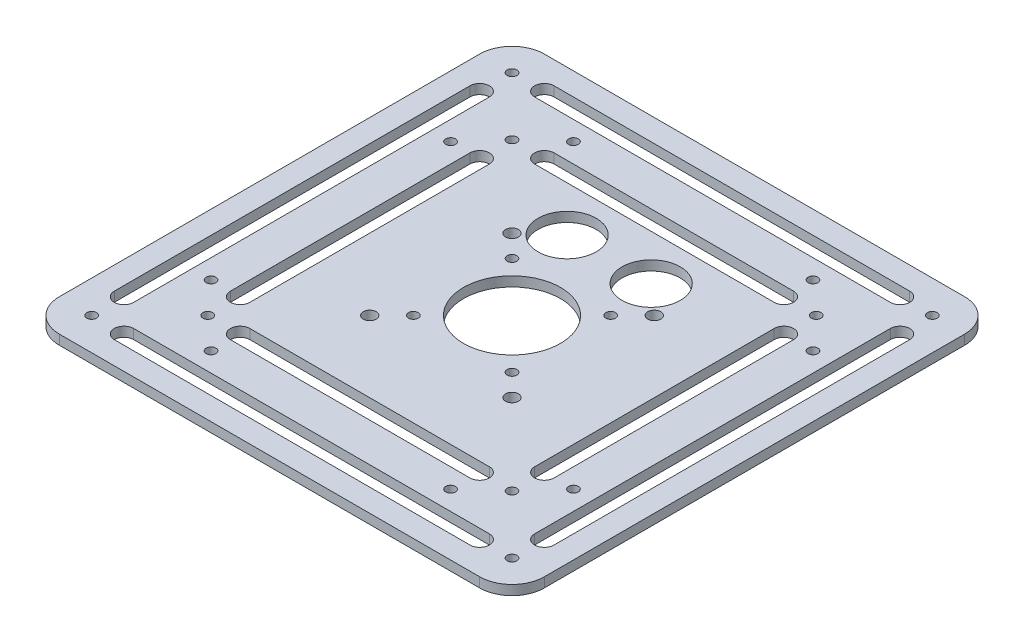
SolidWorks part; units mm, degrees
ref_plane "Front Plane" through (0, 0, 0) normal (0, 0, 1) x (1, 0, 0)
ref_plane "Top Plane" through (0, 0, 0) normal (0, 1, 0) x (1, 0, 0)
ref_plane "Right Plane" through (0, 0, 0) normal (1, 0, 0) x (0, 0, -1)
sketch "Sketch1" plane through (0, 0, 0) normal (0, 1, 0) x (1, 0, 0)
  line L0 (0, 0) -> (0, 75) construction
  line L1 (-65, -75) -> (65, -75)
  line L2 (-75, -65) -> (-75, 65)
  line L3 (-65, 75) -> (65, 75)
  line L4 (75, -65) -> (75, 65)
  line L5 (-75, -75) -> (75, 75) construction
  line L6 (-75, 75) -> (75, -75) construction
  line L7 (0, 0) -> (0, -75) construction
  line L8 (0, 0) -> (75, 0) construction
  line L9 (0, 0) -> (-75, 0) construction
  line L10 (-47.0395, 37.0395) -> (-47.0395, -37.0395) construction
  line L11 (-44.0395, 37.0395) -> (-44.0395, -37.0395)
  line L12 (-50.0395, 37.0395) -> (-50.0395, -37.0395)
  line L13 (47.0395, 37.0395) -> (47.0395, -37.0395) construction
  line L14 (44.0395, 37.0395) -> (44.0395, -37.0395)
  line L15 (50.0395, 37.0395) -> (50.0395, -37.0395)
  line L16 (-37.0395, 47.0395) -> (37.0395, 47.0395) construction
  line L17 (-37.0395, 44.0395) -> (37.0395, 44.0395)
  line L18 (-37.0395, 50.0395) -> (37.0395, 50.0395)
  line L19 (37.0395, -47.0395) -> (-37.0395, -47.0395) construction
  line L20 (37.0395, -44.0395) -> (-37.0395, -44.0395)
  line L21 (37.0395, -50.0395) -> (-37.0395, -50.0395)
  line L22 (-65, 55) -> (-65, -55) construction
  line L23 (-62, 55) -> (-62, -55)
  line L24 (-68, 55) -> (-68, -55)
  line L25 (65, 55) -> (65, -55) construction
  line L26 (62, 55) -> (62, -55)
  line L27 (68, 55) -> (68, -55)
  line L28 (-55, 65) -> (55, 65) construction
  line L29 (-55, 62) -> (55, 62)
  line L30 (-55, 68) -> (55, 68)
  line L31 (55, -65) -> (-55, -65) construction
  line L32 (55, -62) -> (-55, -62)
  line L33 (55, -68) -> (-55, -68)
  arc A0 (-65, -75) -> (-75, -65) centre (-65, -65) cw
  arc A1 (65, -75) -> (75, -65) centre (65, -65) ccw
  arc A2 (65, 75) -> (75, 65) centre (65, 65) cw
  arc A3 (-75, 65) -> (-65, 75) centre (-65, 65) cw
  circle A4 centre (65, 65) radius 1.5
  circle A5 centre (47.0395, 47.0395) radius 1.5
  circle A6 centre (-65, 65) radius 1.5
  circle A7 centre (-47.0395, 47.0395) radius 1.5
  circle A8 centre (65, -65) radius 1.5
  circle A9 centre (47.0395, -47.0395) radius 1.5
  circle A10 centre (-65, -65) radius 1.5
  circle A11 centre (-47.0395, -47.0395) radius 1.5
  circle A12 centre (0, 0) radius 15
  arc A13 (-44.0395, 37.0395) -> (-50.0395, 37.0395) centre (-47.0395, 37.0395) ccw
  arc A14 (-50.0395, -37.0395) -> (-44.0395, -37.0395) centre (-47.0395, -37.0395) ccw
  arc A15 (44.0395, 37.0395) -> (50.0395, 37.0395) centre (47.0395, 37.0395) cw
  arc A16 (50.0395, -37.0395) -> (44.0395, -37.0395) centre (47.0395, -37.0395) cw
  arc A17 (-37.0395, 44.0395) -> (-37.0395, 50.0395) centre (-37.0395, 47.0395) cw
  arc A18 (37.0395, 50.0395) -> (37.0395, 44.0395) centre (37.0395, 47.0395) cw
  arc A19 (37.0395, -44.0395) -> (37.0395, -50.0395) centre (37.0395, -47.0395) cw
  arc A20 (-37.0395, -50.0395) -> (-37.0395, -44.0395) centre (-37.0395, -47.0395) cw
  arc A21 (-62, 55) -> (-68, 55) centre (-65, 55) ccw
  arc A22 (-68, -55) -> (-62, -55) centre (-65, -55) ccw
  arc A23 (62, 55) -> (68, 55) centre (65, 55) cw
  arc A24 (68, -55) -> (62, -55) centre (65, -55) cw
  arc A25 (-55, 62) -> (-55, 68) centre (-55, 65) cw
  arc A26 (55, 68) -> (55, 62) centre (55, 65) cw
  arc A27 (55, -62) -> (55, -68) centre (55, -65) cw
  arc A28 (-55, -68) -> (-55, -62) centre (-55, -65) cw
  circle A29 centre (-56.0395, 37.0395) radius 1.5
  circle A30 centre (-56.0395, -37.0395) radius 1.5
  circle A31 centre (56.0395, -37.0395) radius 1.5
  circle A32 centre (56.0395, 37.0395) radius 1.5
  circle A33 centre (-37.0395, 56.0395) radius 1.5
  circle A34 centre (37.0395, 56.0395) radius 1.5
  circle A35 centre (-37.0395, -56.0395) radius 1.5
  circle A36 centre (37.0395, -56.0395) radius 1.5
  circle A37 centre (-15.25, 15.25) radius 1.5
  circle A38 centre (15.25, 15.25) radius 1.5
  circle A39 centre (-15.25, -15.25) radius 1.5
  circle A40 centre (15.25, -15.25) radius 1.5
  circle A41 centre (-13, 30.0395) radius 9
  circle A42 centre (13, 30.0395) radius 9
  circle A43 centre (-22, 22) radius 2
  circle A44 centre (22, 22) radius 2
  circle A45 centre (22, -22) radius 2
  circle A46 centre (-22, -22) radius 2
  point P0 (0, 0)
  point P38 (-47.0395, 0)
  point P45 (47.0395, 0)
  point P52 (0, 47.0395)
  point P59 (0, -47.0395)
  point P66 (-65, 0)
  point P73 (65, 0)
  point P80 (0, 65)
  point P87 (0, -65)
  dimension "D3" = 10
  dimension "D4" = 3
  dimension "D7" = 3
  dimension "D11" = 30
  dimension "D13" = 10
  dimension "D16" = 10
  dimension "D18" = 9
  dimension "D21" = 3
  dimension "D22" = 3
  dimension "D24" = 3
  dimension "D25" = 3
  dimension "D26" = 3
  dimension "D27" = 18
  dimension "D30" = 74.079
  dimension "D31" = 5.9605
  dimension "D33" = 10
  dimension "D34" = 4
  dimension "D1" = 150
  dimension "D2" = 150
  dimension "D5" = 10
  dimension "D6" = 10
  dimension "D8" = 25.4
  dimension "D9" = 94.079
  dimension "D10" = 10
  dimension "D12" = 27.9605
  dimension "D14" = 10
  dimension "D15" = 27.9605
  dimension "D17" = 10
  dimension "D19" = 10
  dimension "D20" = 9
  dimension "D23" = 15.25
  dimension "D28" = 13
  dimension "D29" = 17
  dimension "D32" = 112.079
  dimension "D35" = 22
extrude "Boss-Extrude1" add sketch "Sketch1" along normal blind 3
sketch "Sketch2" plane through (0, 3, 0) normal (0, 1, 0) x (1, 0, 0)
sketch "Sketch3" plane through (0, 3, 0) normal (0, 1, 0) x (1, 0, 0)
